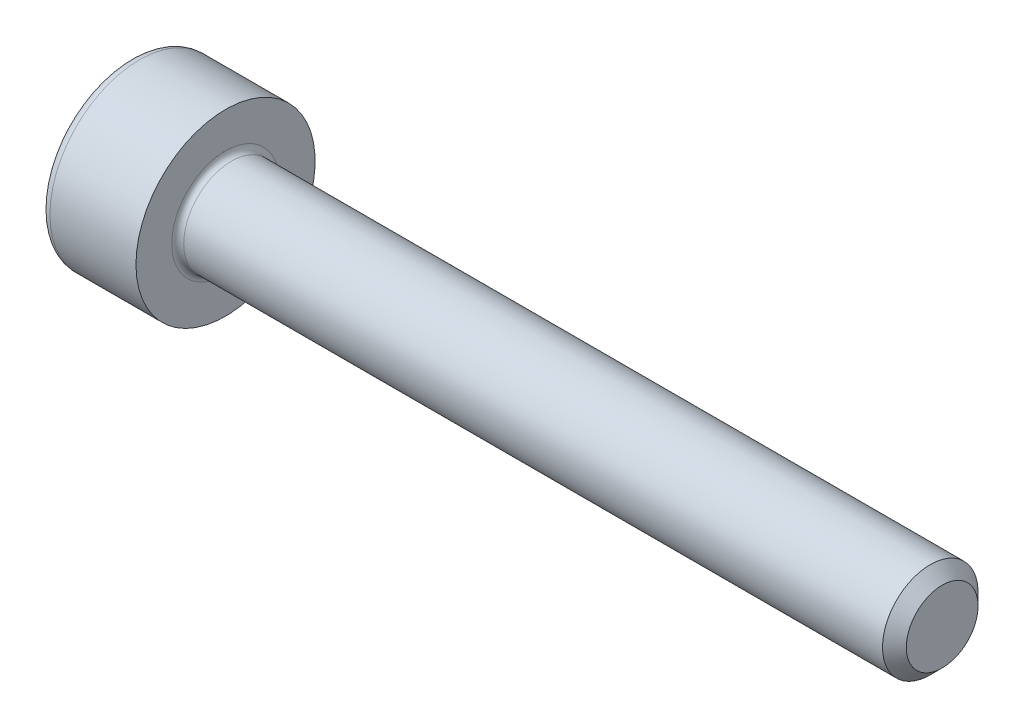
SolidWorks part; units mm, degrees
revolve "Base-Revolve" add sketch "BodySke"
sketch "BodySke" plane through (0, 0, 0) normal (0, 0, 1) x (1, 0, 0)
  line L0 (0, 0) -> (0, 1.5)
  line L1 (0, 1.5) -> (1.6, 1.5)
  line L2 (1.6, 1.5) -> (1.6, 0.8)
  line L3 (1.6, 0.8) -> (13.401, 0.8)
  line L4 (13.6, 0.601) -> (13.6, 0)
  line L5 (13.6, 0) -> (0, 0)
  line L6 (-31.75, 0) -> (127, 0) construction
  line L8 (13.6, 0.601) -> (13.401, 0.8)
  line L10 (13.6, -0.601) -> (13.401, -0.8) construction
  line L11 (1.95, 9.525) -> (1.95, 3.175) construction
  line L12 (1.6, 9.525) -> (1.6, 3.175) construction
  line L13 (-46.4, 9.525) -> (-46.4, 3.175) construction
  dimension "Head_ht" = 1.6
  dimension "Length" = 12
  dimension "Body_ch_ang" = 45
  dimension "Diameter" = 1.6
  dimension "Minor_dia" = 1.202
  dimension "Advance" = 0.35
  dimension "Thread_nom" = 12
  dimension "Thread_length" = 60
  dimension "Head_dia" = 3
cosmetic thread "ThreadCosmetic" [suppressed]
fillet "Fillet1" radius 0.1 1 edges at (1.6, 0, 0.8)
fillet "Fillet2" radius 0.16 1 edges at (0, 0, 1.5)
ref_plane "Plane1" through (0, 0, 0) normal (0, 0, 1) x (1, 0, 0)
ref_plane "Plane2" through (0, 0, 0) normal (0, 1, 0) x (1, 0, 0)
ref_plane "Plane3" through (0, 0, 0) normal (1, 0, 0) x (0, 0, -1)
sketch "Sketch2" plane through (0, 0, 0) normal (0, 0, 1) x (1, 0, 0)
  line L0 (0, 0.76) -> (0.7, 0.76)
  line L1 (0.7, 0.76) -> (1.1388, 0)
  line L2 (-31.75, 0) -> (127, 0) construction
  line L3 (1.1388, 0) -> (0, 0)
  line L4 (0, 0) -> (0, 0.76)
  line L6 (0, 0) -> (47.625, 0) construction
  dimension "D1" = 0.76
  dimension "D2" = 60
  dimension "Depth" = 0.7
revolve "Hex-PreBroach" cut sketch "Sketch2" angle 360 about L6
sketch "Sketch3" plane through (0, 0, 0) normal (-1, 0, 0) x (0, 0.5, 0.866)
  line L0 (0.4388, 0.76) -> (-0.4388, 0.76)
  line L1 (-0.4388, 0.76) -> (-0.8776, 0)
  line L2 (0.4388, 0.76) -> (0.8776, 0)
  line L3 (0.4388, -0.76) -> (0.8776, 0)
  line L4 (0.4388, -0.76) -> (-0.4388, -0.76)
  line L5 (-0.4388, -0.76) -> (-0.8776, 0)
  dimension "D1" = 0.76
  dimension "D2" = 0.76
  dimension "Hex_size" = 1.52
extrude "Hex" cut sketch "Sketch3" against normal blind 0.7
sketch "ThdSchSke" plane through (0, 0, 0) normal (0, 0, 1) x (1, 0, 0)
  line L0 (2.65, -0.601) -> (2.5107, -0.8)
  line L1 (2.65, -0.601) -> (2.7893, -0.8)
  line L2 (2.7893, -0.8) -> (2.7893, -1)
  line L3 (-3.175, 0) -> (5.1513, 0) construction
  line L4 (0, 1.34) -> (0, -1.34) construction
  line L5 (2.7893, -1) -> (2.5107, -1)
  line L6 (2.5107, -1) -> (2.5107, -0.8)
  dimension "Thread_minor" = 1.202
  dimension "Diameter" = 1.6
  dimension "Start" = 2.65
revolve "ThreadSchematic" [suppressed] cut sketch "ThdSchSke" angle 360 about L3
pattern_linear "ThdSchPat" [suppressed]
equation "\"D2@Sketch3\" = \"Hex_size@Sketch3\" / 2"
equation "\"D1@Sketch3\" = \"Hex_size@Sketch3\" / 2"
equation "\"D1@Sketch2\" = \"Hex_size@Sketch3\" / 2"
equation "\"Thread_minor@ThreadCosmetic\"  =  \"Minor_dia@BodySke\""
equation "\"Depth@Sketch2\" =  \"Key_eng@Hex\""
equation "\"Thread_length@ThreadCosmetic\" = ((sgn( (\"Length@BodySke\" - \"Advance@BodySke\" * 3.0) - \"Thread_nom@BodySke\" )-1)*( (\"Length@BodySke\" - \"Advance@BodySke\" * 3.0) - \"Thread_nom@BodySke\" ))/-2+ \"Thread_nom@BodySke\""
equation "\"Thread_minor@ThdSchSke\" = \"Minor_dia@BodySke\""
equation "\"Diameter@ThdSchSke\" = \"Diameter@BodySke\""
equation "\"Overcut@ThdSchSke\" = \"Diameter@BodySke\" * 1.25"
equation "\"Start@ThdSchSke\" = \"Head_ht@BodySke\" + \"Length@BodySke\" - \"Thread_length@ThreadCosmetic\"  '---Non-countersunk---"
equation "\"Num_threads@ThdSchPat\" = int( \"Thread_length@ThreadCosmetic\" / \"Advance@BodySke\" + 0.999 )  + 1"
equation "\"Advance@ThdSchPat\" = \"Thread_length@ThreadCosmetic\" /  (\"Num_threads@ThdSchPat\" - 1) 'relax it"
equation "\"Num_threads@ThdSchPat\" = \"Num_threads@ThdSchPat\" - sgn( \"Num_threads@ThdSchPat\" - 1) '---chamfered tips only---"
